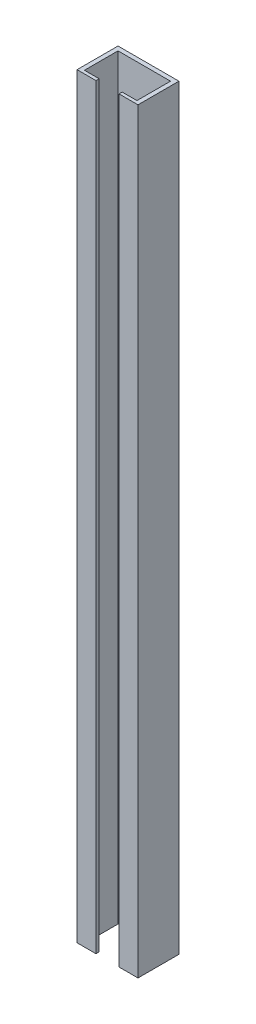
SolidWorks part; units mm, degrees
ref_plane "Front Plane" through (0, 0, 0) normal (0, 0, 1) x (1, 0, 0)
ref_plane "Top Plane" through (0, 0, 0) normal (0, 1, 0) x (1, 0, 0)
ref_plane "Right Plane" through (0, 0, 0) normal (1, 0, 0) x (0, 0, -1)
sketch "Sketch1" plane through (0, 0, 0) normal (0, 1, 0) x (1, 0, 0)
  line L4 (-184.15, 228.6) -> (184.15, 228.6)
  line L5 (184.15, 228.6) -> (184.15, -19.05)
  line L6 (184.15, -19.05) -> (69.85, -19.05)
  line L7 (69.85, -19.05) -> (69.85, 0)
  line L8 (69.85, 0) -> (158.75, 0)
  line L9 (158.75, 0) -> (158.75, 203.2)
  line L10 (158.75, 203.2) -> (-158.75, 203.2)
  line L11 (-158.75, 203.2) -> (-158.75, 0)
  line L12 (-158.75, 0) -> (-69.85, 0)
  line L13 (-69.85, 0) -> (-69.85, -19.05)
  line L14 (-69.85, -19.05) -> (-184.15, -19.05)
  line L15 (-184.15, -19.05) -> (-184.15, 228.6)
  line L16 (158.75, 0) -> (184.15, 0) construction
  line L17 (-158.75, 0) -> (-184.15, 0) construction
  line L18 (-69.85, 0) -> (69.85, 0) construction
  line L20 (75.3904, 114.3) -> (129.0916, 114.3) construction
  line L21 (75.3904, 114.3) -> (75.3904, 0) construction
  line L22 (75.3904, 0) -> (129.0916, 0) construction
  line L23 (129.0916, 114.3) -> (129.0916, 0) construction
  line L24 (75.3904, 114.3) -> (129.0916, 0) construction
  line L25 (75.3904, 0) -> (129.0916, 114.3) construction
  point P3 (75.3904, 127.0873)
  point P17 (0, 0)
  point P20 (102.241, 57.15)
  dimension "D1" = 19.05
  dimension "D2" = 25.4
  dimension "D3" = 25.4
  dimension "D4" = 139.7
  dimension "D5" = 88.9
  dimension "D6" = 203.2
  dimension "D7" = 114.3
extrude "Boss-Extrude1" add sketch "Sketch1" along normal mid plane 4572
